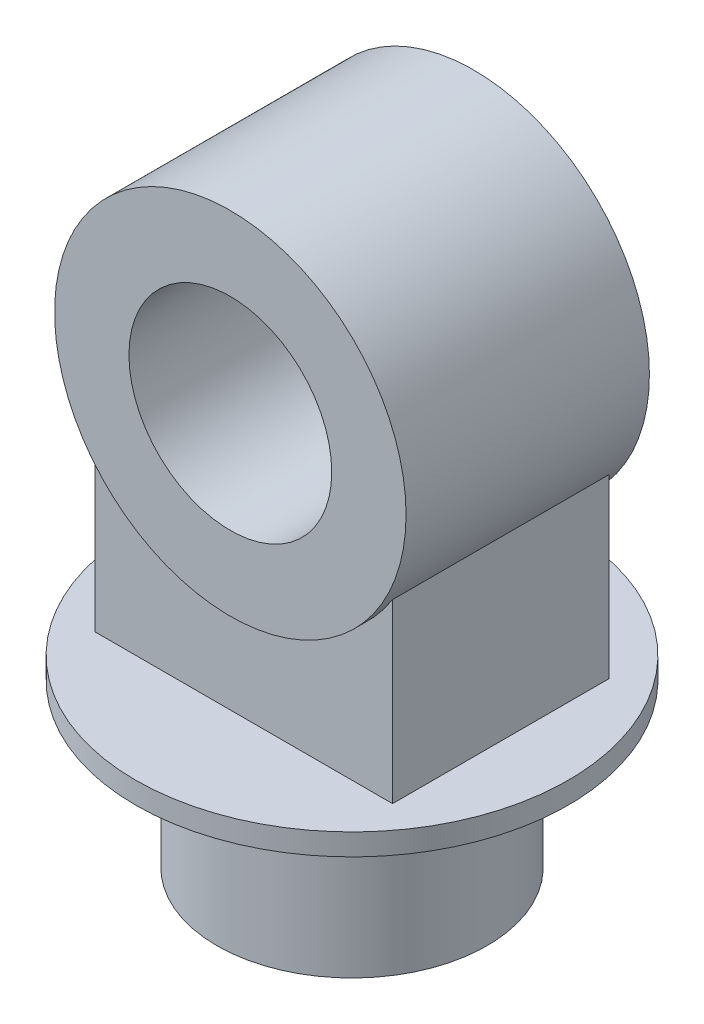
SolidWorks part; units mm, degrees
ref_plane "Front Plane" through (0, 0, 0) normal (0, 0, 1) x (1, 0, 0)
ref_plane "Top Plane" through (0, 0, 0) normal (0, 1, 0) x (1, 0, 0)
ref_plane "Right Plane" through (0, 0, 0) normal (1, 0, 0) x (0, 0, -1)
sketch "Sketch1" plane through (0, 0, 0) normal (0, 1, 0) x (1, 0, 0)
  circle A0 centre (0, 0) radius 100
  dimension "D1" = 200
extrude "Boss-Extrude1" add sketch "Sketch1" along normal blind 120
sketch "Sketch2" plane through (0, 120, 0) normal (0, 1, 0) x (1, 0, 0)
  circle A0 centre (0, 0) radius 160
  dimension "D1" = 320
extrude "Boss-Extrude2" add sketch "Sketch2" along normal blind 16
sketch "Sketch3" plane through (0, 0, 0) normal (0, 0, 1) x (1, 0, 0)
  line L0 (0, 0) -> (0, 338.066) construction
  line L1 (0, 336) -> (0, 136)
  line L2 (160, 136) -> (-160, 136) construction
  circle A0 centre (0, 336) radius 75
  circle A1 centre (0, 336) radius 130
  dimension "D1" = 150
  dimension "D2" = 260
  dimension "D3" = 200
extrude "Boss-Extrude3" add sketch "Sketch3" along normal mid plane 180 separate body
sketch "Sketch4" plane through (0, 136, 0) normal (0, 1, 0) x (1, 0, 0)
  line L1 (-110, 80) -> (110, 80)
  line L2 (-110, 80) -> (-110, -80)
  line L3 (-110, -80) -> (110, -80)
  line L4 (110, 80) -> (110, -80)
  line L5 (-110, 80) -> (110, -80) construction
  line L6 (-110, -80) -> (110, 80) construction
  point P0 (0, 0)
  dimension "D1" = 160
  dimension "D2" = 220
extrude "Boss-Extrude4" add sketch "Sketch4" along normal up to next
